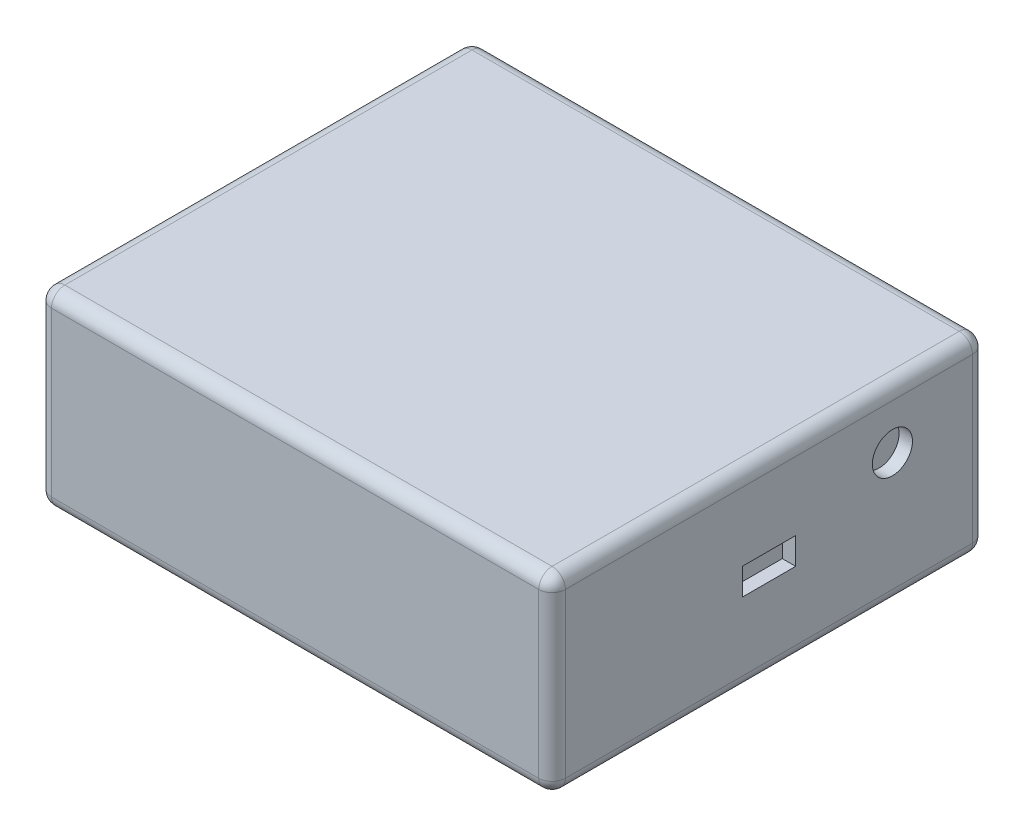
SolidWorks part; units mm, degrees
ref_plane "Plan de face" through (0, 0, 0) normal (0, 0, 1) x (1, 0, 0)
ref_plane "Plan de dessus" through (0, 0, 0) normal (0, 1, 0) x (1, 0, 0)
ref_plane "Plan de droite" through (0, 0, 0) normal (1, 0, 0) x (0, 0, -1)
sketch "Esquisse1" plane through (0, 0, 0) normal (0, 1, 0) x (1, 0, 0)
  line L1 (-38.5, -32.5) -> (38.5, -32.5)
  line L2 (-38.5, -32.5) -> (-38.5, 32.5)
  line L3 (-38.5, 32.5) -> (38.5, 32.5)
  line L4 (38.5, -32.5) -> (38.5, 32.5)
  line L5 (-38.5, -32.5) -> (38.5, 32.5) construction
  line L6 (-38.5, 32.5) -> (38.5, -32.5) construction
  point P0 (0, 0)
  dimension "D1" = 77
  dimension "D2" = 65
extrude "Boss.-Extru.1" add sketch "Esquisse1" along normal blind 28.5
fillet "Congé2" radius 2 12 edges at (38.5, 28.5, 0) (38.5, 0, 0) (0, 28.5, 32.5) (38.5, 14.25, 32.5) (0, 0, 32.5) (-38.5, 28.5, 0) (-38.5, 14.25, 32.5) (-38.5, 0, 0) (38.5, 14.25, -32.5) (0, 28.5, -32.5) (-38.5, 14.25, -32.5) (0, 0, -32.5)
sketch "Esquisse2" plane through (38.5, 0, 0) normal (1, 0, 0) x (0, 0, -1)
  line L0 (32.5, 14.25) -> (-32.5, 14.25) construction
  line L1 (32.5, 26.5) -> (32.5, 2) construction
  line L2 (-32.5, 2) -> (-32.5, 26.5) construction
  line L4 (-4, 12.25) -> (4, 12.25)
  line L5 (-4, 12.25) -> (-4, 16.25)
  line L6 (-4, 16.25) -> (4, 16.25)
  line L7 (4, 12.25) -> (4, 16.25)
  line L8 (-4, 12.25) -> (4, 16.25) construction
  line L9 (-4, 16.25) -> (4, 12.25) construction
  circle A0 centre (18.5, 19.75) radius 3
  point P6 (0, 14.25)
  point P15 (0, 0)
  dimension "D3" = 6
  dimension "D1" = 4
  dimension "D2" = 8
  dimension "D4" = 18.5
  dimension "D5" = 5.5
extrude "Enlèv. mat.-Extru.1" cut sketch "Esquisse2" against normal blind 2
